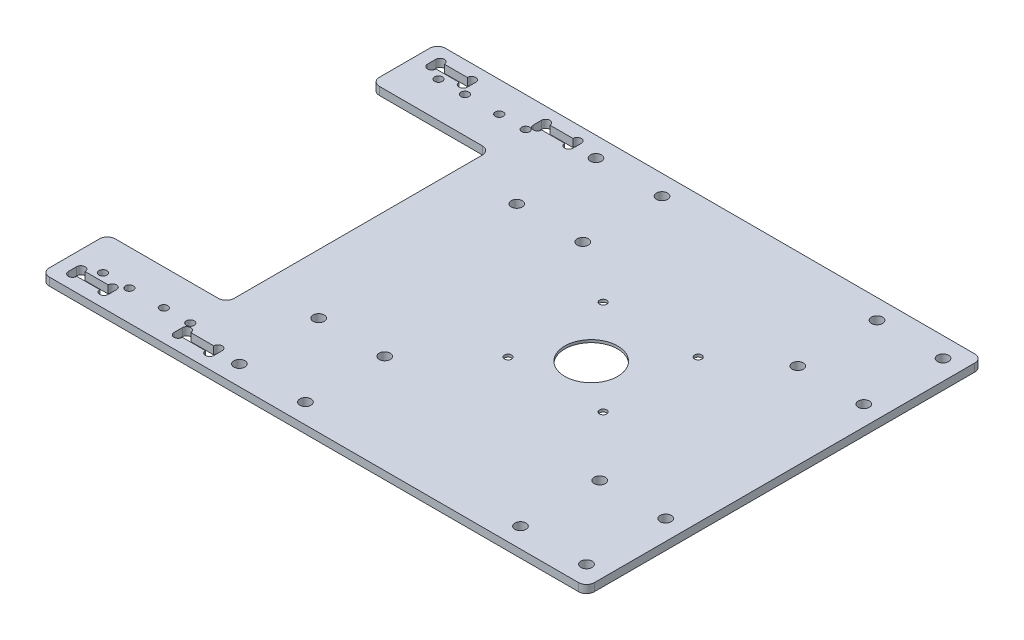
SolidWorks part; units mm, degrees
material "Thornel Mat VMA"
ref_plane "前视基准面" through (0, 0, 0) normal (0, 0, 1) x (1, 0, 0)
ref_plane "上视基准面" through (0, 0, 0) normal (0, 1, 0) x (1, 0, 0)
ref_plane "右视基准面" through (0, 0, 0) normal (1, 0, 0) x (0, 0, -1)
other "Configuration Table"
sketch "草图1" plane through (0, 0, 0) normal (0, 1, 0) x (1, 0, 0)
  line L0 (0, 0) -> (0, 27.529) construction
  line L1 (0, 0) -> (24.492, 0) construction
  line L2 (-73.2, 75) -> (-73.2, -75) construction
  line L3 (-133.2, -75) -> (73.2, -75)
  line L4 (-133.2, -75) -> (-133.2, 75)
  line L5 (-133.2, 75) -> (73.2, 75)
  line L6 (73.2, -75) -> (73.2, 75)
  line L7 (-133.2, -75) -> (73.2, 75) construction
  line L8 (-133.2, 75) -> (73.2, -75) construction
  circle A0 centre (65.7, 67.5) radius 2.1
  circle A1 centre (65.7, -67.5) radius 2.1
  circle A2 centre (-65.7, -67.5) radius 2.1
  circle A3 centre (-65.7, 67.5) radius 2.1
  circle A4 centre (-65.7, 37.5) radius 2.1 construction
  circle A5 centre (-40.7, 37.5) radius 2.1 construction
  circle A6 centre (-40.7, 67.5) radius 2.1 construction
  circle A7 centre (-40.7, -67.5) radius 2.1 construction
  circle A8 centre (-40.7, -37.5) radius 2.1 construction
  circle A9 centre (-65.7, -37.5) radius 2.1 construction
  circle A10 centre (40.7, -67.5) radius 2.1 construction
  circle A11 centre (40.7, -37.5) radius 2.1 construction
  circle A12 centre (65.7, -37.5) radius 2.1 construction
  circle A13 centre (65.7, 37.5) radius 2.1 construction
  circle A14 centre (40.7, 37.5) radius 2.1 construction
  circle A15 centre (40.7, 67.5) radius 2.1 construction
  circle A16 centre (-65.7, 37.5) radius 2.1
  circle A17 centre (-40.7, 37.5) radius 2.1
  circle A18 centre (-40.7, 67.5) radius 2.1
  circle A19 centre (-40.7, -67.5) radius 2.1
  circle A20 centre (-40.7, -37.5) radius 2.1
  circle A21 centre (-65.7, -37.5) radius 2.1
  circle A22 centre (40.7, -67.5) radius 2.1
  circle A23 centre (40.7, -37.5) radius 2.1
  circle A24 centre (65.7, -37.5) radius 2.1
  circle A25 centre (65.7, 37.5) radius 2.1
  circle A26 centre (40.7, 37.5) radius 2.1
  circle A27 centre (40.7, 67.5) radius 2.1
  circle A29 centre (-98.4, 63.575) radius 1.5
  circle A30 centre (-98.4, 63.575) radius 1.5
  circle A31 centre (-88.4, 63.575) radius 1.5
  circle A32 centre (-88.4, 63.575) radius 1.5
  circle A33 centre (-111.4, 63.575) radius 1.5
  circle A34 centre (-111.4, 63.575) radius 1.5
  circle A35 centre (-121.4, 63.575) radius 1.5
  circle A36 centre (-121.4, 63.575) radius 1.5
  circle A37 centre (-121.4, -63.475) radius 1.5
  circle A38 centre (-121.4, -63.475) radius 1.5
  circle A39 centre (-111.4, -63.475) radius 1.5
  circle A40 centre (-111.4, -63.475) radius 1.5
  circle A41 centre (-98.4, -63.425) radius 1.5
  circle A42 centre (-98.4, -63.425) radius 1.5
  circle A43 centre (-88.4, -63.425) radius 1.5
  circle A44 centre (-88.4, -63.425) radius 1.5
  point P6 (-30, 0)
  dimension "D1" = 135
  dimension "D2" = 131.4
  dimension "D3" = 4.2
  dimension "D4" = 7.5
  dimension "D5" = 7.5
  dimension "D6" = 60
  dimension "D7" = 7.5
  dimension "D8" = 0
  dimension "D9" = 0
  dimension "D10" = 0
  dimension "D11" = 0
  dimension "D12" = 0
  dimension "D13" = 0
  dimension "D14" = 0
  dimension "D15" = 0
extrude "凸台-拉伸1" add sketch "草图1" along normal blind 3
sketch "草图2" plane through (0, 0, 0) normal (0, 1, 0) x (1, 0, 0)
  line L0 (-128.4, -68) -> (-113.3, -68) construction
  line L1 (-125.2, -66.425) -> (-116.5, -66.425)
  line L2 (-128.4, -66.425) -> (-128.4, -69.575)
  line L3 (-125.2, -69.575) -> (-116.5, -69.575)
  line L4 (-113.3, -66.425) -> (-113.3, -69.575)
  line L5 (-120.85, -69.575) -> (-120.85, -66.425) construction
  line L6 (-85.2, -66.425) -> (-76.5, -66.425)
  line L7 (-88.4, -66.425) -> (-88.4, -69.575)
  line L8 (-85.2, -69.575) -> (-76.5, -69.575)
  line L9 (-73.3, -66.425) -> (-73.3, -69.575)
  line L10 (-88.4, -68) -> (-73.3, -68) construction
  line L11 (-80.85, -69.575) -> (-80.85, -66.425) construction
  line L12 (-133.2, 75) -> (-133.2, -75) construction
  line L14 (-133.2, 0) -> (73.2, 0) construction
  line L15 (73.2, -75) -> (73.2, 75) construction
  line L16 (-80.85, 69.575) -> (-80.85, 66.425) construction
  line L17 (-88.4, 68) -> (-73.3, 68) construction
  line L18 (-120.85, 69.575) -> (-120.85, 66.425) construction
  line L19 (-128.4, 68) -> (-113.3, 68) construction
  line L20 (-73.3, 66.425) -> (-73.3, 69.575)
  line L21 (-85.2, 69.575) -> (-76.5, 69.575)
  line L22 (-88.4, 66.425) -> (-88.4, 69.575)
  line L23 (-85.2, 66.425) -> (-76.5, 66.425)
  line L24 (-113.3, 66.425) -> (-113.3, 69.575)
  line L25 (-125.2, 69.575) -> (-116.5, 69.575)
  line L26 (-128.4, 66.425) -> (-128.4, 69.575)
  line L27 (-125.2, 66.425) -> (-116.5, 66.425)
  arc A0 (-128.4, -66.425) -> (-125.2, -66.425) centre (-126.8, -66.425) cw
  arc A1 (-113.3, -66.425) -> (-116.5, -66.425) centre (-114.9, -66.425) ccw
  arc A2 (-113.3, -69.575) -> (-116.5, -69.575) centre (-114.9, -69.575) cw
  arc A3 (-128.4, -69.575) -> (-125.2, -69.575) centre (-126.8, -69.575) ccw
  arc A4 (-88.4, -66.425) -> (-85.2, -66.425) centre (-86.8, -66.425) cw
  arc A5 (-73.3, -66.425) -> (-76.5, -66.425) centre (-74.9, -66.425) ccw
  arc A6 (-73.3, -69.575) -> (-76.5, -69.575) centre (-74.9, -69.575) cw
  arc A7 (-88.4, -69.575) -> (-85.2, -69.575) centre (-86.8, -69.575) ccw
  arc A8 (-88.4, 69.575) -> (-85.2, 69.575) centre (-86.8, 69.575) cw
  arc A9 (-73.3, 69.575) -> (-76.5, 69.575) centre (-74.9, 69.575) ccw
  arc A10 (-73.3, 66.425) -> (-76.5, 66.425) centre (-74.9, 66.425) cw
  arc A11 (-88.4, 66.425) -> (-85.2, 66.425) centre (-86.8, 66.425) ccw
  arc A12 (-128.4, 69.575) -> (-125.2, 69.575) centre (-126.8, 69.575) cw
  arc A13 (-113.3, 69.575) -> (-116.5, 69.575) centre (-114.9, 69.575) ccw
  arc A14 (-113.3, 66.425) -> (-116.5, 66.425) centre (-114.9, 66.425) cw
  arc A15 (-128.4, 66.425) -> (-125.2, 66.425) centre (-126.8, 66.425) ccw
  circle A16 centre (-65.7, 67.5) radius 2.1 construction
  dimension "D3" = 1.6
  dimension "D6" = 7.6
  dimension "D1" = 3.15
  dimension "D2" = 15.1
  dimension "D5" = 40
  dimension "D7" = 136
  dimension "D4" = 2
extrude "切除-拉伸1" cut sketch "草图2" along normal through all
fillet "圆角1" radius 3 4 edges at (73.2, 1.5, 75) (-133.2, 1.5, 75) (73.2, 1.5, -75) (-133.2, 1.5, -75)
sketch "草图4" plane through (0, 0, 0) normal (0, 1, 0) x (1, 0, 0)
  line L0 (-133.2, 72) -> (-133.2, -72) construction
  line L1 (-120.7, -27.5) -> (60.7, -27.5)
  line L2 (-125.7, -22.5) -> (-125.7, 22.5)
  line L3 (-120.7, 27.5) -> (60.7, 27.5)
  line L4 (65.7, -22.5) -> (65.7, 22.5)
  line L5 (-125.7, -27.5) -> (65.7, 27.5) construction
  line L6 (-125.7, 27.5) -> (65.7, -27.5) construction
  line L7 (65.7, 37.5) -> (65.7, -37.5) construction
  arc A0 (-120.7, -27.5) -> (-125.7, -22.5) centre (-120.7, -22.5) cw
  arc A1 (60.7, -27.5) -> (65.7, -22.5) centre (60.7, -22.5) ccw
  arc A2 (60.7, 27.5) -> (65.7, 22.5) centre (60.7, 22.5) cw
  arc A3 (-125.7, 22.5) -> (-120.7, 27.5) centre (-120.7, 22.5) cw
  circle A4 centre (40.7, 37.5) radius 2.1 construction
  point P0 (-30, 0)
  dimension "D1" = 5
  dimension "D2" = 10
  dimension "D3" = 7.5
extrude "切除-拉伸2" cut sketch "草图4" along normal blind 2
sketch "草图6" plane through (0, 3, 0) normal (0, 1, 0) x (1, 0, 0)
  circle A0 centre (0, 0) radius 10
  dimension "D1" = 20
extrude "切除-拉伸3" cut sketch "草图6" against normal blind 10
sketch "草图7" plane through (0, 3, 0) normal (0, 1, 0) x (1, 0, 0)
  line L0 (-133.2, 50) -> (-88.2, 50)
  line L1 (-133.2, 72) -> (-133.2, -72) construction
  line L2 (-88.2, 50) -> (-88.2, -50)
  line L3 (-88.2, -50) -> (-133.2, -50)
  line L4 (-133.2, -50) -> (-133.2, 50)
  line L5 (70.2, 75) -> (-130.2, 75) construction
  line L6 (-130.2, -75) -> (70.2, -75) construction
  dimension "D1" = 25
  dimension "D2" = 25
  dimension "D3" = 45
extrude "切除-拉伸4" cut sketch "草图7" against normal blind 10
fillet "圆角2" radius 3 4 edges at (-88.2, 1.5, -50) (-88.2, 1.5, 50) (-133.2, 1.5, 50) (-133.2, 1.5, -50)
sketch "草图8" plane through (0, 2, 0) normal (0, -1, 0) x (1, 0, 0)
  arc A8 (17.543, 14.3849) -> (20.243, 14.3849) centre (18.893, 14.3849) ccw
  arc A9 (20.243, 14.3849) -> (17.543, 14.3849) centre (18.893, 14.3849) ccw
  arc A10 (-18.457, 14.3849) -> (-15.757, 14.3849) centre (-17.107, 14.3849) ccw
  arc A11 (-15.757, 14.3849) -> (-18.457, 14.3849) centre (-17.107, 14.3849) ccw
  arc A12 (-15.757, -21.6151) -> (-18.457, -21.6151) centre (-17.107, -21.6151) ccw
  arc A13 (-18.457, -21.6151) -> (-15.757, -21.6151) centre (-17.107, -21.6151) ccw
  arc A14 (20.243, -21.6151) -> (17.543, -21.6151) centre (18.893, -21.6151) ccw
  arc A15 (17.543, -21.6151) -> (20.243, -21.6151) centre (18.893, -21.6151) ccw
extrude "切除-拉伸5" cut sketch "草图8" against normal blind 10
